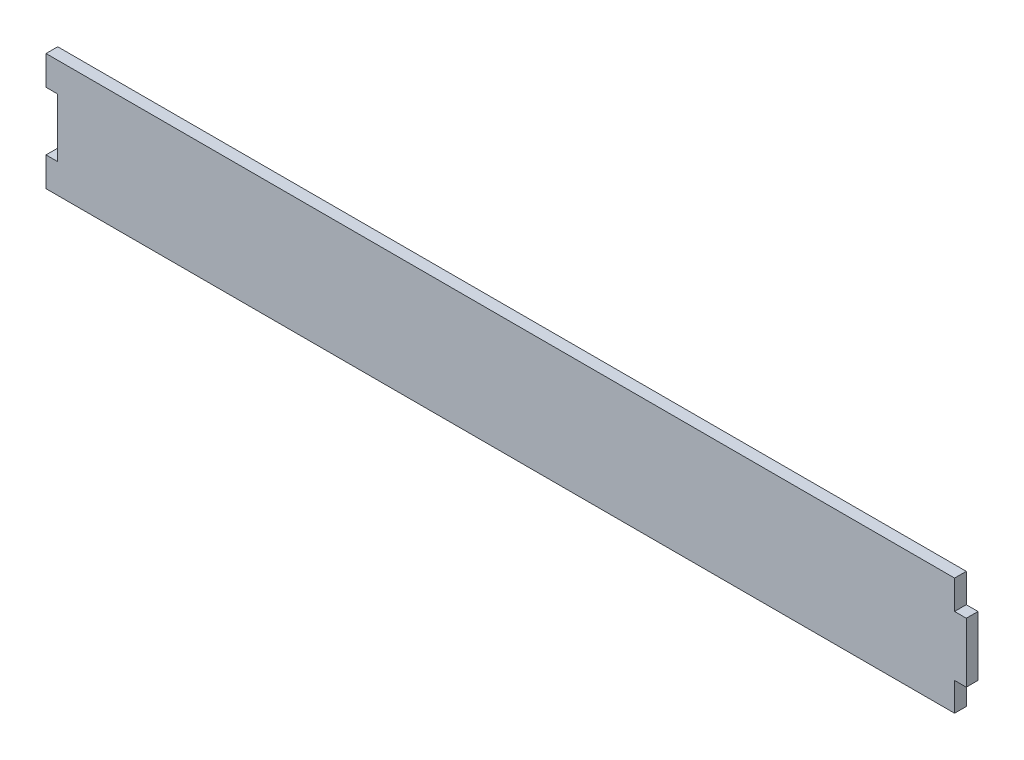
SolidWorks part; units mm, degrees
ref_plane "Ebene vorne" through (0, 0, 0) normal (0, 0, 1) x (1, 0, 0)
ref_plane "Ebene oben" through (0, 0, 0) normal (0, 1, 0) x (1, 0, 0)
ref_plane "Ebene rechts" through (0, 0, 0) normal (1, 0, 0) x (0, 0, -1)
sketch "Skizze1" plane through (0, 0, 0) normal (0, 0, 1) x (1, 0, 0)
  line L1 (0, 0) -> (393, 0)
  line L2 (0, 0) -> (0, 50)
  line L3 (0, 50) -> (393, 50)
  line L4 (393, 0) -> (393, 50)
  dimension "D1" = 50
  dimension "D2" = 393
extrude "Aufsatz-Linear austragen1" add sketch "Skizze1" along normal blind 5 contours L3 L4 L1 L2
sketch "Skizze2" plane through (0, 0, 5) normal (0, 0, 1) x (1, 0, 0)
  line L0 (0, 0) -> (0, 50) construction
  line L1 (-15.1752, 37.5) -> (5, 37.5)
  line L2 (-15.1752, 37.5) -> (-15.1752, 12.5)
  line L3 (-15.1752, 12.5) -> (5, 12.5)
  line L4 (5, 37.5) -> (5, 12.5)
  line L5 (0, 50) -> (393, 50) construction
  line L6 (0, 0) -> (393, 0) construction
  line L7 (388, 60.7982) -> (440.9588, 60.7982)
  line L8 (388, 60.7982) -> (388, 37.65)
  line L9 (388, 37.65) -> (440.9588, 37.65)
  line L10 (440.9588, 60.7982) -> (440.9588, 37.65)
  line L11 (388, 12.15) -> (418.9078, 12.15)
  line L12 (388, 12.15) -> (388, -45.6182)
  line L13 (388, -45.6182) -> (418.9078, -45.6182)
  line L14 (418.9078, 12.15) -> (418.9078, -45.6182)
  dimension "D1" = 5
  dimension "D2" = 25
  dimension "D3" = 12.5
  dimension "D4" = 25.5
  dimension "D5" = 12.15
  dimension "D6" = 12.35
  dimension "D7" = 5
  dimension "D8" = 5
extrude "Schnitt-Linear austragen1" cut sketch "Skizze2" against normal blind 5
